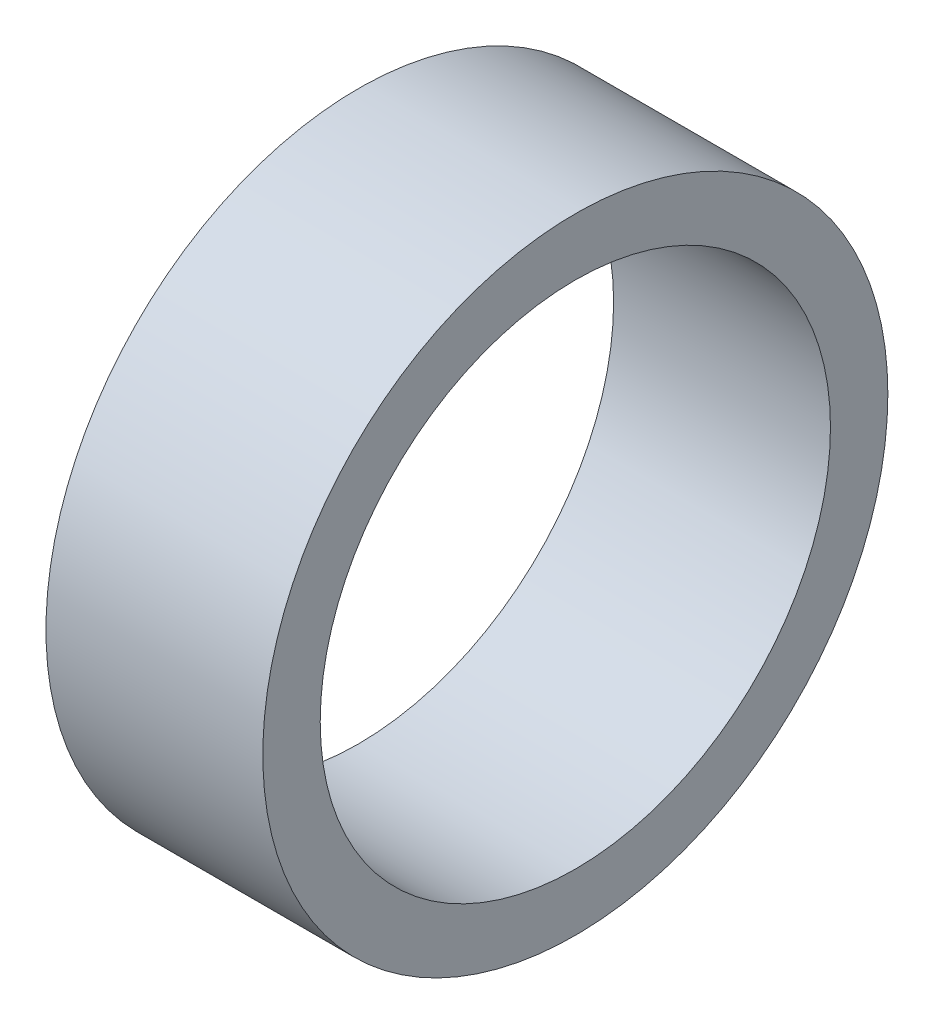
SolidWorks part; units mm, degrees
ref_plane "正面" through (0, 0, 0) normal (1, 0, 0) x (0, 1, 0)
ref_plane "平面" through (0, 0, 0) normal (0, 0, 1) x (0, 1, 0)
ref_plane "右側面" through (0, 0, 0) normal (0, 1, 0) x (-1, 0, 0)
sketch "ｽｹｯﾁ1" plane through (0, 0, 0) normal (1, 0, 0) x (0, 1, 0)
  circle A0 centre (0, 0) radius 12.25
  circle A1 centre (0, 0) radius 10
  dimension "D1" = 20
  dimension "D2" = 24.5
extrude "ﾎﾞｽ - 押し出し1" add sketch "ｽｹｯﾁ1" along normal blind 8.5 contours A1 | A0
